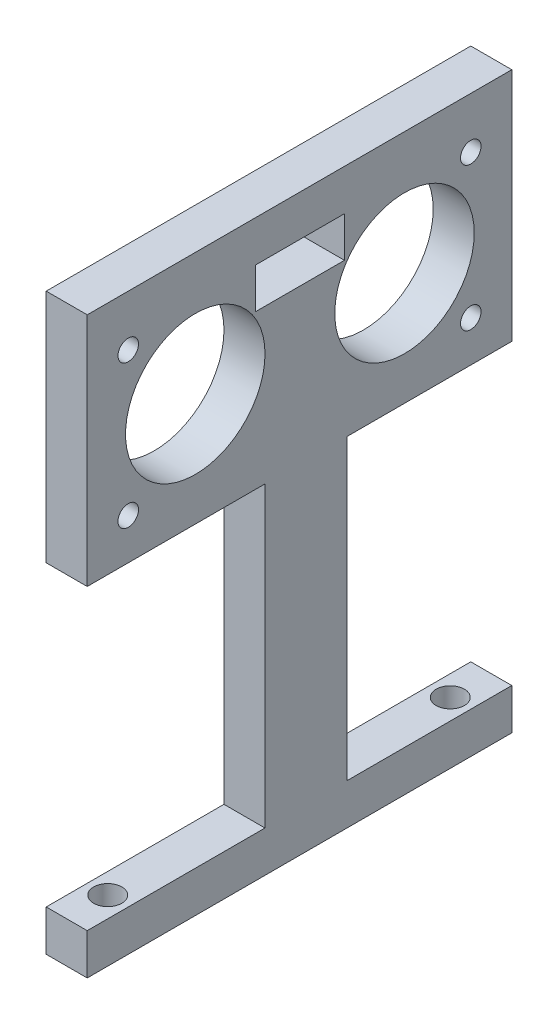
SolidWorks part; units mm, degrees
ref_plane "Front Plane" through (0, 0, 0) normal (0, 0, 1) x (1, 0, 0)
ref_plane "Top Plane" through (0, 0, 0) normal (0, 1, 0) x (1, 0, 0)
ref_plane "Right Plane" through (0, 0, 0) normal (1, 0, 0) x (0, 0, -1)
sketch "Sketch1" plane through (0, 0, 0) normal (1, 0, 0) x (0, 0, -1)
  line L0 (62.997, -55.8297) -> (88.397, -55.8297)
  line L2 (-64.003, 27.8375) -> (-64.003, -55.8297)
  line L4 (62.997, 27.8375) -> (62.997, -55.8297)
  line L6 (-89.403, -65.9897) -> (-89.403, -55.8297)
  line L7 (-89.403, -55.8297) -> (-64.003, -55.8297)
  line L8 (88.397, -65.9897) -> (88.397, -55.8297)
  line L9 (-89.403, -65.9897) -> (88.397, -65.9897)
  line L10 (-64.003, -13.9961) -> (75.8155, -13.9961) construction
  line L16 (-64.003, 27.8375) -> (62.997, 27.8375)
extrude "Boss-Extrude1" add sketch "Sketch1" along normal blind 5.08
sketch "Sketch2" plane through (0, 0, 0) normal (1, 0, 0) x (0, 0, -1)
  line L6 (-89.403, -65.9897) -> (88.397, -65.9897) construction
  line L7 (50.297, -65.9897) -> (-51.303, -65.9897)
  line L8 (50.297, -65.9897) -> (50.297, -55.8297)
  line L9 (50.297, -55.8297) -> (-51.303, -55.8297)
  line L10 (-51.303, -65.9897) -> (-51.303, -55.8297)
  line L11 (62.997, -55.8297) -> (62.997, 27.8375) construction
  line L12 (-64.003, 27.8375) -> (-64.003, -55.8297) construction
  dimension "D1" = 12.7
  dimension "D2" = 12.7
extrude "Cut-Extrude3" cut sketch "Sketch2" along normal blind 22.86
sketch "Sketch8" plane through (0, 0, 0) normal (1, 0, 0) x (0, 0, -1)
  line L0 (62.997, -55.8297) -> (62.997, 27.8375) construction
  circle A0 centre (12.197, -10.1006) radius 8.636
  circle A1 centre (-13.711, -10.1006) radius 8.636
  dimension "D1" = 17.272
  dimension "D2" = 50.8
  dimension "D3" = 25.908
  dimension "D4" = 10.1006
sketch "Sketch9" plane through (0, 0, 0) normal (1, 0, 0) x (0, 0, -1)
  line L0 (-23.458, -10.1006) -> (24.1858, -10.1006) construction
  line L1 (-23.458, 0.1544) -> (-23.458, -20.3556) construction
  line L2 (-0.803, 0.1544) -> (-0.803, -23.8564) construction
  line L3 (21.852, 0.1544) -> (-23.458, 0.1544) construction
  circle A0 centre (-22.0102, -1.2239) radius 1.27
  circle A1 centre (-22.0102, -18.9772) radius 1.27
  circle A2 centre (20.4042, -18.9772) radius 1.27
  circle A3 centre (20.4042, -1.2239) radius 1.27
  dimension "D2" = 2.54
  dimension "D1" = 1.4478
  dimension "D3" = 1.2239
sketch "Sketch13" plane through (0, 0, 0) normal (1, 0, 0) x (0, 0, -1)
  line L0 (21.852, 0.1544) -> (-23.458, 0.1544) construction
  line L1 (-6.2582, 0) -> (4.7654, 0)
  line L2 (-6.2582, 0) -> (-6.2582, -5.0038)
  line L3 (-6.2582, -5.0038) -> (4.7654, -5.0038)
  line L4 (4.7654, 0) -> (4.7654, -5.0038)
  dimension "D1" = 5.0038
  dimension "D2" = 0.1544
  dimension "D3" = 11.0236
  dimension "D4" = 6.2582
extrude "Cut-Extrude4" cut sketch "Sketch9" along normal blind 25.908
extrude "Cut-Extrude5" cut sketch "Sketch13" along normal blind 25.908
extrude "Cut-Extrude6" cut sketch "Sketch8" along normal blind 25.908
sketch "Sketch14" plane through (0, 0, 0) normal (1, 0, 0) x (0, 0, -1)
  line L1 (-27.0902, 5.08) -> (25.4842, 5.08)
  line L2 (-27.0902, 5.08) -> (-27.0902, -24.0572)
  line L3 (-27.0902, -24.0572) -> (25.4842, -24.0572)
  line L4 (25.4842, 5.08) -> (25.4842, -24.0572)
  line L5 (-111.6829, 44.5623) -> (100.5201, 44.5623)
  line L6 (-111.6829, 44.5623) -> (-111.6829, -77.9583)
  line L7 (-111.6829, -77.9583) -> (100.5201, -77.9583)
  line L8 (100.5201, 44.5623) -> (100.5201, -77.9583)
  circle A0 centre (-22.0102, -18.9772) radius 1.27 construction
  circle A1 centre (20.4042, -18.9772) radius 1.27 construction
  dimension "D2" = 5.08
  dimension "D3" = 5.08
  dimension "D4" = 5.08
  dimension "D1" = 5.08
extrude "Cut-Extrude7" cut sketch "Sketch14" along normal blind 25.908
sketch "Sketch15" plane through (0, 0, 0) normal (1, 0, 0) x (0, 0, -1)
  line L0 (-27.0902, -66.04) -> (-27.0902, -22.3178)
  line L2 (-27.0902, -66.04) -> (25.4842, -66.04)
  line L3 (25.4842, -66.04) -> (25.4842, -22.3178)
  line L4 (-27.0902, -24.0572) -> (-27.0902, 5.08) construction
  line L5 (-27.0902, -22.3178) -> (25.4842, -22.3178)
  dimension "D1" = 66.04
  dimension "D2" = 25.4842
  dimension "D3" = 22.3178
extrude "Boss-Extrude2" add sketch "Sketch15" along normal blind 5.08
sketch "Sketch17" plane through (0, 0, 0) normal (1, 0, 0) x (0, 0, -1)
  line L0 (0, 0) -> (0, -71.7288) construction
  line L1 (-30.6594, -24.0572) -> (-5.08, -24.0572)
  line L2 (-30.6594, -24.0572) -> (-30.6594, -60.96)
  line L3 (-30.6594, -60.96) -> (-5.08, -60.96)
  line L4 (-5.08, -24.0572) -> (-5.08, -60.96)
  line L5 (-27.0902, -66.04) -> (25.4842, -66.04) construction
  line L6 (30.6594, -24.0572) -> (5.08, -24.0572)
  line L7 (30.6594, -24.0572) -> (30.6594, -60.96)
  line L8 (30.6594, -60.96) -> (5.08, -60.96)
  line L9 (5.08, -24.0572) -> (5.08, -60.96)
  circle A0 centre (-22.0102, -18.9772) radius 1.27 construction
  dimension "D1" = 5.08
  dimension "D2" = 5.08
  dimension "D3" = 5.08
  dimension "D4" = 30.6594
extrude "Cut-Extrude8" cut sketch "Sketch17" along normal blind 10.16
ref_plane "Plane1" through (0, -66.04, 0) normal (0, 1, 0) x (1, 0, 0)
sketch "Sketch18" plane through (0, -66.04, 0) normal (0, 1, 0) x (1, 0, 0)
  line L0 (5.08, -27.0902) -> (0, -27.0902) construction
  line L1 (5.08, -27.0902) -> (5.08, 25.4842) construction
  line L2 (0, -0.803) -> (20.3338, -0.803) construction
  line L3 (0, -27.0902) -> (0, 25.4842) construction
  circle A0 centre (2.54, -22.0102) radius 1.7526
  circle A1 centre (2.54, 20.4042) radius 1.7526
  dimension "D1" = 3.5052
  dimension "D2" = 5.08
  dimension "D3" = 2.54
extrude "Cut-Extrude9" cut sketch "Sketch18" along normal blind 10.16
